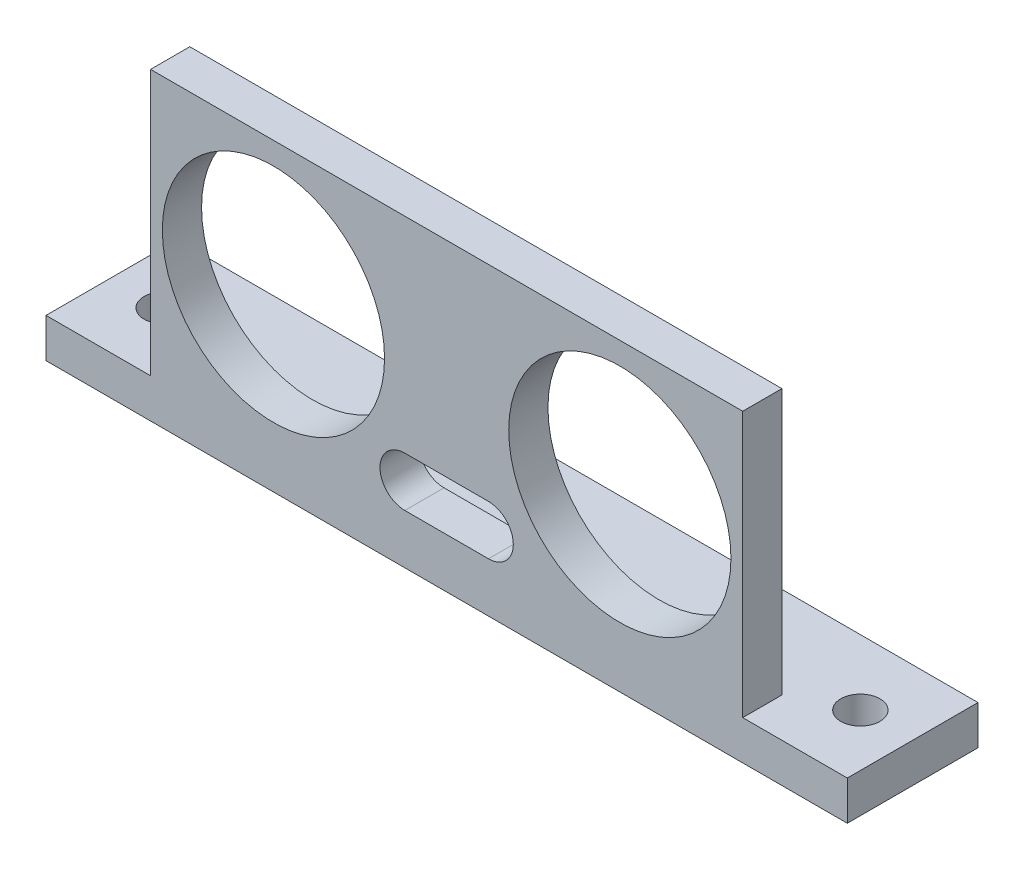
SolidWorks part; units mm, degrees
ref_plane "Front Plane" through (0, 0, 0) normal (0, 0, 1) x (1, 0, 0)
ref_plane "Top Plane" through (0, 0, 0) normal (0, 1, 0) x (1, 0, 0)
ref_plane "Right Plane" through (0, 0, 0) normal (1, 0, 0) x (0, 0, -1)
sketch "Sketch1" plane through (0, 0, 0) normal (0, 0, 1) x (1, 0, 0)
  line L1 (98.6394, -11.1578) -> (-71.3606, -11.1578)
  line L2 (98.6394, -11.1578) -> (98.6394, -8.1578)
  line L3 (98.6394, -8.1578) -> (-71.3606, -8.1578)
  line L4 (-71.3606, -11.1578) -> (-71.3606, -8.1578)
  line L5 (98.6394, -11.1578) -> (-71.3606, -8.1578) construction
  line L6 (98.6394, -8.1578) -> (-71.3606, -11.1578) construction
  point P0 (13.6394, -9.6578)
extrude "Boss-Extrude1" add sketch "Sketch1" along normal blind 10
sketch "Sketch2" plane through (0, -8.1578, 0) normal (0, 1, 0) x (1, 0, 0)
  line L0 (98.6394, -10) -> (-71.3606, -10) construction
  line L1 (-53.3606, -7) -> (-8.0606, -7)
  line L2 (-53.3606, -7) -> (-53.3606, -10)
  line L3 (-53.3606, -10) -> (-8.0606, -10)
  line L4 (-8.0606, -7) -> (-8.0606, -10)
  line L5 (-53.3606, -7) -> (-8.0606, -10) construction
  line L6 (-53.3606, -10) -> (-8.0606, -7) construction
  line L7 (-71.3606, -10) -> (-71.3606, 0) construction
  point P0 (-30.7106, -8.5)
  dimension "D1" = 0
  dimension "D2" = 18
sketch "Sketch4" plane through (0, -8.1578, 0) normal (0, 1, 0) x (1, 0, 0)
  line L0 (-71.3606, -10) -> (-71.3606, 0) construction
  line L1 (98.6394, -10) -> (98.6394, 0) construction
  circle A0 centre (-63.3606, -4.9385) radius 1.2
  circle A1 centre (90.6394, -5.2832) radius 1.2
  dimension "D1" = 8
  dimension "D2" = 8
extrude "Cut-Extrude1" cut sketch "Sketch4" against normal blind 21
extrude "Boss-Extrude6" add sketch "Sketch2" along normal blind 20.3
sketch "Sketch5" plane through (0, 0, 7) normal (0, 0, -1) x (-1, 0, 0)
  line L0 (8.0606, 12.1422) -> (8.0606, -8.1578) construction
  line L1 (53.3606, 12.1422) -> (53.3606, -8.1578) construction
  line L2 (8.0606, 12.1422) -> (53.3606, 12.1422) construction
  line L3 (27.5106, -5.4578) -> (33.9106, -5.4578) construction
  line L4 (27.5106, -3.5578) -> (33.9106, -3.5578)
  line L5 (27.5106, -7.3578) -> (33.9106, -7.3578)
  circle A0 centre (17.4606, 1.9422) radius 8.5
  circle A1 centre (43.9606, 1.9422) radius 8.5
  arc A2 (27.5106, -3.5578) -> (27.5106, -7.3578) centre (27.5106, -5.4578) ccw
  arc A3 (33.9106, -7.3578) -> (33.9106, -3.5578) centre (33.9106, -5.4578) ccw
  point P12 (30.7106, -5.4578)
  dimension "D1" = 26.5
  dimension "D6" = 1.9
  dimension "D2" = 9.4
  dimension "D3" = 9.4
  dimension "D4" = 10.2
  dimension "D5" = 10.2
  dimension "D7" = 6.4
  dimension "D8" = 15.7
  dimension "D9" = 19.45
  dimension "D10" = 19.45
extrude "Cut-Extrude2" cut sketch "Sketch5" against normal blind 20.3
sketch "Sketch6" plane through (0, -8.1578, 0) normal (0, 1, 0) x (1, 0, 0)
  line L0 (98.6394, -10) -> (-8.0606, -10) construction
  line L1 (35.3394, -7) -> (80.6394, -7)
  line L2 (35.3394, -7) -> (35.3394, -10)
  line L3 (35.3394, -10) -> (80.6394, -10)
  line L4 (80.6394, -7) -> (80.6394, -10)
  line L5 (35.3394, -7) -> (80.6394, -10) construction
  line L6 (35.3394, -10) -> (80.6394, -7) construction
  line L7 (98.6394, -10) -> (98.6394, 0) construction
  point P0 (57.9894, -8.5)
  point P9 (80.6394, -8.5)
  dimension "D1" = 0
  dimension "D2" = 18
extrude "Boss-Extrude7" add sketch "Sketch6" along normal blind 20.3
sketch "Sketch7" plane through (0, 0, 10) normal (0, 0, 1) x (1, 0, 0)
  line L0 (35.3394, 12.1422) -> (35.3394, -8.1578) construction
  line L1 (35.3394, 12.1422) -> (80.6394, 12.1422) construction
  line L3 (-33.9106, -7.3578) -> (-27.5106, -7.3578) construction
  line L4 (-71.3606, -11.1578) -> (98.6394, -11.1578) construction
  line L5 (-53.3606, 12.1422) -> (-53.3606, -8.1578) construction
  line L6 (54.8394, -5.4578) -> (61.2394, -5.4578) construction
  line L7 (54.8394, -3.5578) -> (61.2394, -3.5578)
  line L8 (54.8394, -7.3578) -> (61.2394, -7.3578)
  circle A0 centre (44.7394, 1.9422) radius 8.5
  circle A1 centre (71.2394, 1.9422) radius 8.5
  circle A2 centre (-43.9606, 1.9422) radius 8.5 construction
  circle A3 centre (-17.4606, 1.9422) radius 8.5 construction
  arc A5 (-33.9106, -3.5578) -> (-33.9106, -7.3578) centre (-33.9106, -5.4578) ccw construction
  arc A6 (54.8394, -3.5578) -> (54.8394, -7.3578) centre (54.8394, -5.4578) ccw
  arc A7 (61.2394, -7.3578) -> (61.2394, -3.5578) centre (61.2394, -5.4578) ccw
  point P23 (58.0394, -5.4578)
  dimension "D1" = 26.5
  dimension "D6" = 3.8
  dimension "D7" = 19.45
  dimension "D9" = 19.5
  dimension "D10" = 1.9
  dimension "D2" = 26.5
  dimension "D3" = 9.4
  dimension "D4" = 10.2
  dimension "D5" = 10.2
  dimension "D8" = 3.8
extrude "Cut-Extrude3" cut sketch "Sketch7" against normal through all
sketch "Sketch12" plane through (0, -8.1578, 0) normal (0, 1, 0) x (1, 0, 0)
  line L0 (98.6394, -10) -> (98.6394, 0) construction
  line L1 (9.9394, 4.0024) -> (98.6394, 4.0024)
  line L2 (9.9394, 4.0024) -> (9.9394, -13.2393)
  line L3 (9.9394, -13.2393) -> (98.6394, -13.2393)
  line L4 (98.6394, 4.0024) -> (98.6394, -13.2393)
  line L5 (9.9394, 4.0024) -> (98.6394, -13.2393) construction
  line L6 (9.9394, -13.2393) -> (98.6394, 4.0024) construction
  line L7 (-8.0606, -10) -> (-8.0606, -7) construction
  point P0 (54.2894, -4.6184)
  dimension "D1" = 0
  dimension "D2" = 18
extrude "Cut-Extrude5" cut sketch "Sketch12" against normal through all both and the other way through all
sketch "Sketch13" plane through (0, -8.1578, 0) normal (0, 1, 0) x (1, 0, 0)
  line L0 (-53.3606, -7) -> (-53.3606, -10) construction
  line L1 (-90.4965, 23.215) -> (-53.3606, 23.215)
  line L2 (-90.4965, 23.215) -> (-90.4965, -15.2472)
  line L3 (-90.4965, -15.2472) -> (-53.3606, -15.2472)
  line L4 (-53.3606, 23.215) -> (-53.3606, -15.2472)
  line L5 (-90.4965, 23.215) -> (-53.3606, -15.2472) construction
  line L6 (-90.4965, -15.2472) -> (-53.3606, 23.215) construction
  line L7 (30.4015, -40.9439) -> (-8.0606, -40.9439)
  line L8 (30.4015, -40.9439) -> (30.4015, 6.8023)
  line L9 (30.4015, 6.8023) -> (-8.0606, 6.8023)
  line L10 (-8.0606, -40.9439) -> (-8.0606, 6.8023)
  line L11 (30.4015, -40.9439) -> (-8.0606, 6.8023) construction
  line L12 (30.4015, 6.8023) -> (-8.0606, -40.9439) construction
  line L13 (-8.0606, -10) -> (-8.0606, -7) construction
  point P0 (-71.9286, 3.9839)
  point P5 (11.1705, -17.0708)
  point P12 (-53.3606, -8.5)
  dimension "D1" = 0
  dimension "D2" = 0
extrude "Cut-Extrude6" cut sketch "Sketch13" against normal through all both and the other way through all
sketch "Sketch15" plane through (0, -11.1578, 0) normal (0, -1, 0) x (1, 0, 0)
  line L0 (-53.3606, 10) -> (-8.0606, 10) construction
  line L1 (-53.3606, 0) -> (-61.3606, 0)
  line L2 (-53.3606, 0) -> (-53.3606, 10)
  line L3 (-53.3606, 10) -> (-61.3606, 10)
  line L4 (-61.3606, 0) -> (-61.3606, 10)
  line L5 (-53.3606, 0) -> (-61.3606, 10) construction
  line L6 (-53.3606, 10) -> (-61.3606, 0) construction
  line L7 (-0.0606, 0) -> (-8.0606, 0)
  line L8 (-0.0606, 0) -> (-0.0606, 10)
  line L9 (-0.0606, 10) -> (-8.0606, 10)
  line L10 (-8.0606, 0) -> (-8.0606, 10)
  line L11 (-0.0606, 0) -> (-8.0606, 10) construction
  line L12 (-0.0606, 10) -> (-8.0606, 0) construction
  line L13 (-53.3606, 0) -> (-8.0606, 0) construction
  line L14 (-53.3606, 10) -> (-53.3606, 0) construction
  line L15 (-8.0606, 7) -> (-8.0606, 0) construction
  point P0 (-57.3606, 5)
  point P5 (-4.0606, 5)
  dimension "D1" = 0
  dimension "D2" = 0
  dimension "D3" = 0
  dimension "D4" = 0
  dimension "D5" = 0
  dimension "D6" = 0
extrude "Boss-Extrude9" add sketch "Sketch15" against normal blind 3
sketch "Sketch16" plane through (0, -11.1578, 0) normal (0, -1, 0) x (-1, 0, 0)
  line L0 (61.3606, -10) -> (61.3606, 0) construction
  line L1 (61.3606, 0) -> (0.0606, 0) construction
  line L2 (61.3606, -10) -> (0.0606, -10) construction
  line L3 (0.0606, 0) -> (0.0606, -10) construction
  circle A0 centre (57.3606, -5) radius 1.5
  circle A1 centre (4.0606, -5) radius 1.5
  dimension "D1" = 4
  dimension "D2" = 5
  dimension "D3" = 5
  dimension "D4" = 4
extrude "Cut-Extrude7" cut sketch "Sketch16" against normal through all both and the other way through all
